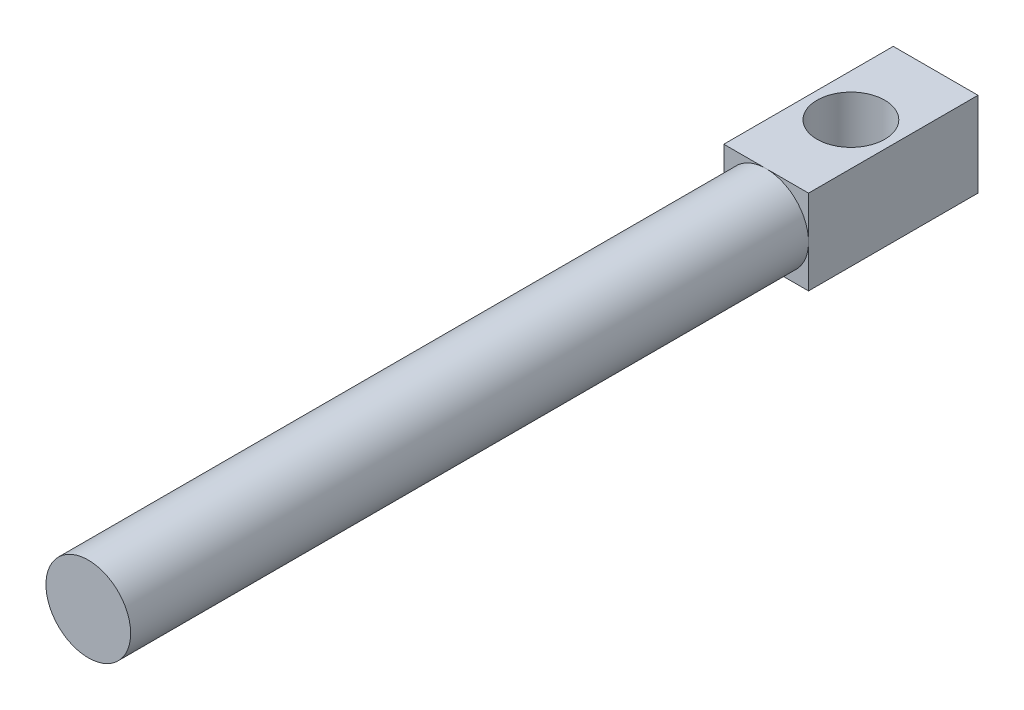
SolidWorks part; units mm, degrees
ref_plane "Front Plane" through (0, 0, 0) normal (0, 0, 1) x (1, 0, 0)
ref_plane "Top Plane" through (0, 0, 0) normal (0, 1, 0) x (1, 0, 0)
ref_plane "Right Plane" through (0, 0, 0) normal (1, 0, 0) x (0, 0, -1)
other "Center of Mass"
sketch "Sketch1" plane through (0, 0, 0) normal (0, 0, 1) x (1, 0, 0)
  circle A0 centre (0, 0) radius 7.5
extrude "Boss-Extrude1" add sketch "Sketch1" along normal blind 150
ref_plane "Plane3" through (0, 0, 0) normal (0, 1, 0) x (1, 0, 0)
sketch "Sketch4" plane through (0, 0, 0) normal (0, 1, 0) x (1, 0, 0)
  line L0 (0, 0) -> (0, -150) construction
  line L1 (7.5, 0) -> (-7.5, 0) construction
  line L2 (-7.5, -150) -> (7.5, -150) construction
  line L4 (7.5, -30) -> (-7.5, -30)
  line L5 (7.5, -30) -> (7.5, 0)
  line L6 (7.5, 0) -> (-7.5, 0)
  line L7 (-7.5, -30) -> (-7.5, 0)
  line L8 (7.5, -30) -> (-7.5, 0) construction
  line L9 (7.5, 0) -> (-7.5, -30) construction
  point P6 (0, -30)
  point P7 (0, -15)
  point P8 (0, -15)
  dimension "D1" = 30
  dimension "D2" = 15
extrude "Boss-Extrude2" add sketch "Sketch4" along normal mid plane 15
sketch "Sketch5" plane through (0, 7.5, 0) normal (0, 1, 0) x (1, 0, 0)
  line L0 (-7.5, 0) -> (7.5, -30) construction
  line L1 (7.5, 0) -> (-7.5, -30) construction
  circle A0 centre (0, -15) radius 6
extrude "Cut-Extrude2" cut sketch "Sketch5" against normal through all
sketch "Sketch6" plane through (0, 0, 0) normal (0, 1, 0) x (1, 0, 0)
  line L0 (0, 0) -> (0, -30) construction
  line L1 (-7.5, -15) -> (7.5, -15) construction
  line L2 (-7.5, 0) -> (-7.5, -30) construction
  line L3 (7.5, -30) -> (7.5, 0) construction
  point P10 (0, -15)
sketch "Sketch7" plane through (0, 0, 0) normal (0, 1, 0) x (1, 0, 0)
  line L0 (0, 0) -> (0, -150) construction
  line L1 (-7.5, -150) -> (7.5, -150) construction
  point P5 (0, -98)
  dimension "D1" = 135
  dimension "D2" = 52
  dimension "D3" = 83
